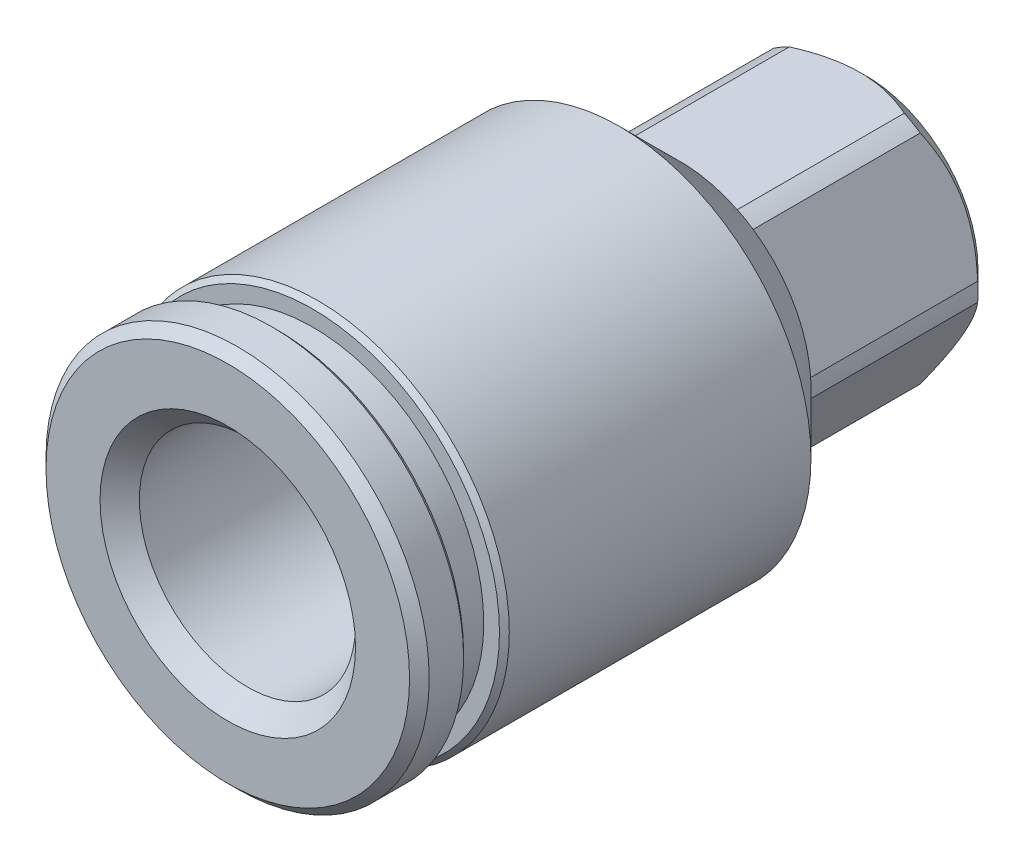
SolidWorks part; units mm, degrees
ref_plane "Front Plane" through (0, 0, 0) normal (0, 0, 1) x (1, 0, 0)
ref_plane "Top Plane" through (0, 0, 0) normal (0, 1, 0) x (1, 0, 0)
ref_plane "Right Plane" through (0, 0, 0) normal (1, 0, 0) x (0, 0, -1)
sketch "Sketch1" plane through (0, 0, 0) normal (1, 0, 0) x (0, 0, -1)
  line L0 (0, 0) -> (65, 0) construction
  line L1 (35, 0) -> (35, 11.7)
  line L2 (34.2, 12.5) -> (30.9439, 12.5)
  line L3 (5, 19) -> (5, 17.4)
  line L4 (28, 11) -> (2, 11)
  line L5 (2, 11) -> (0, 13)
  line L6 (0, 13) -> (0, 18.5)
  line L7 (0, 18.5) -> (1, 19.5)
  line L8 (1, 19.5) -> (4.5, 19.5)
  line L9 (39.85, 19.5) -> (46, 13.35)
  line L10 (28, 11) -> (30.9439, 12.5)
  line L11 (46, 13.35) -> (63, 13.35)
  line L12 (63, 13.35) -> (65, 11.35)
  line L13 (65, 11.35) -> (65, 0)
  line L14 (65, 0) -> (35, 0)
  line L15 (5, 17.4) -> (8.65, 17.4)
  line L16 (8.65, 17.4) -> (8.65, 19)
  line L17 (9.15, 19.5) -> (39.85, 19.5)
  line L18 (8.65, 19) -> (9.15, 19.5)
  line L19 (4.5, 19.5) -> (5, 19)
  arc A0 (35, 11.7) -> (34.2, 12.5) centre (34.2, 11.7) ccw
  point P5 (5, 19.5)
  point P19 (6.825, 17.4)
  point P21 (8.65, 19.5)
  dimension "D15" = 0.8
  dimension "D1" = 65
  dimension "D2" = 45
  dimension "D3" = 2
  dimension "D4" = 45
  dimension "D5" = 13.35
  dimension "D6" = 19
  dimension "D7" = 2
  dimension "D8" = 1
  dimension "D9" = 35
  dimension "D10" = 7
  dimension "D11" = 12.5
  dimension "D12" = 11
  dimension "D13" = 19.5
  dimension "D14" = 27
  dimension "D16" = 3.65
  dimension "D17" = 5
  dimension "D18" = 17.4
revolve "Revolve1" add sketch "Sketch1" angle 360 about L0
sketch "Sketch2" plane through (0, 0, -65) normal (0, 0, -1) x (-1, 0, 0)
  line L1 (-13.8564, 0) -> (-6.9282, -12)
  line L2 (-6.9282, -12) -> (6.9282, -12)
  line L3 (6.9282, -12) -> (13.8564, 0)
  line L4 (13.8564, 0) -> (6.9282, 12)
  line L5 (6.9282, 12) -> (-6.9282, 12)
  line L6 (-6.9282, 12) -> (-13.8564, 0)
  circle A0 centre (0, 0) radius 12 construction
  dimension "D1" = 24
extrude "Cut-Extrude1" cut sketch "Sketch2" against normal blind 19 flip side to cut
